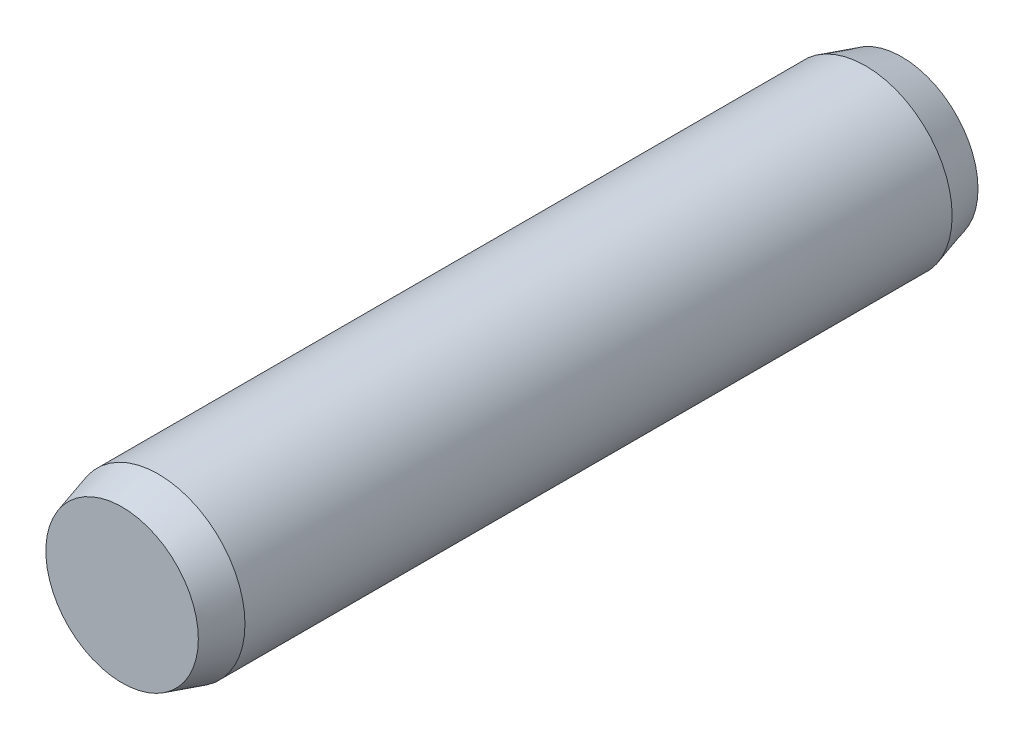
SolidWorks part; units mm, degrees
ref_plane "Front Plane" through (0, 0, 0) normal (0, 0, 1) x (1, 0, 0)
ref_plane "Top Plane" through (0, 0, 0) normal (0, 1, 0) x (1, 0, 0)
ref_plane "Right Plane" through (0, 0, 0) normal (1, 0, 0) x (0, 0, -1)
sketch "Sketch1" plane through (0, 0, 0) normal (0, 0, 1) x (1, 0, 0)
  circle A0 centre (0, 0) radius 1.5875
  point P3 (0, 1.5875)
  dimension "Diameter" = 3.175
sketch "Sketch2" plane through (0, 0, 0) normal (1, 0, 0) x (0, 0, -1)
  line L0 (-7.1438, 0) -> (7.1438, 0) construction
  line L1 (-7.1438, 0) -> (-7.1438, 1.5875)
  line L2 (-7.1438, 1.5875) -> (7.1438, 1.5875)
  line L3 (7.1438, 1.5875) -> (7.1438, 0)
  line L4 (-7.1438, 1.397) -> (-6.4794, 1.5875)
  line L5 (7.1438, 1.397) -> (6.4794, 1.5875)
  dimension "Length" = 14.2875
  dimension "Chamfer Angle" = 16
  dimension "Point Diameter" = 2.794
sketch "Sketch3" plane through (0, 0, 0) normal (1, 0, 0) x (0, 0, -1)
  line L0 (-7.1438, 0) -> (7.1438, 0) construction
  line L1 (7.1438, 1.5875) -> (7.1438, 0) construction
  line L2 (-7.1438, 1.5875) -> (7.1438, 1.5875) construction
  line L3 (-7.1438, 0) -> (-7.1438, 1.5875) construction
  line L4 (-7.1438, 0) -> (7.1438, 0)
  line L5 (7.1438, 1.397) -> (7.1438, 0)
  line L6 (-6.4794, 1.5875) -> (6.4794, 1.5875)
  line L7 (-7.1438, 0) -> (-7.1438, 1.397)
  line L8 (7.1438, 1.397) -> (6.4794, 1.5875) construction
  line L9 (-7.1438, 1.397) -> (-6.4794, 1.5875) construction
  line L10 (7.1438, 1.397) -> (6.4794, 1.5875)
  line L11 (-7.1438, 1.397) -> (-6.4794, 1.5875)
revolve "Revolve1" add sketch "Sketch3" angle 360 about L0
